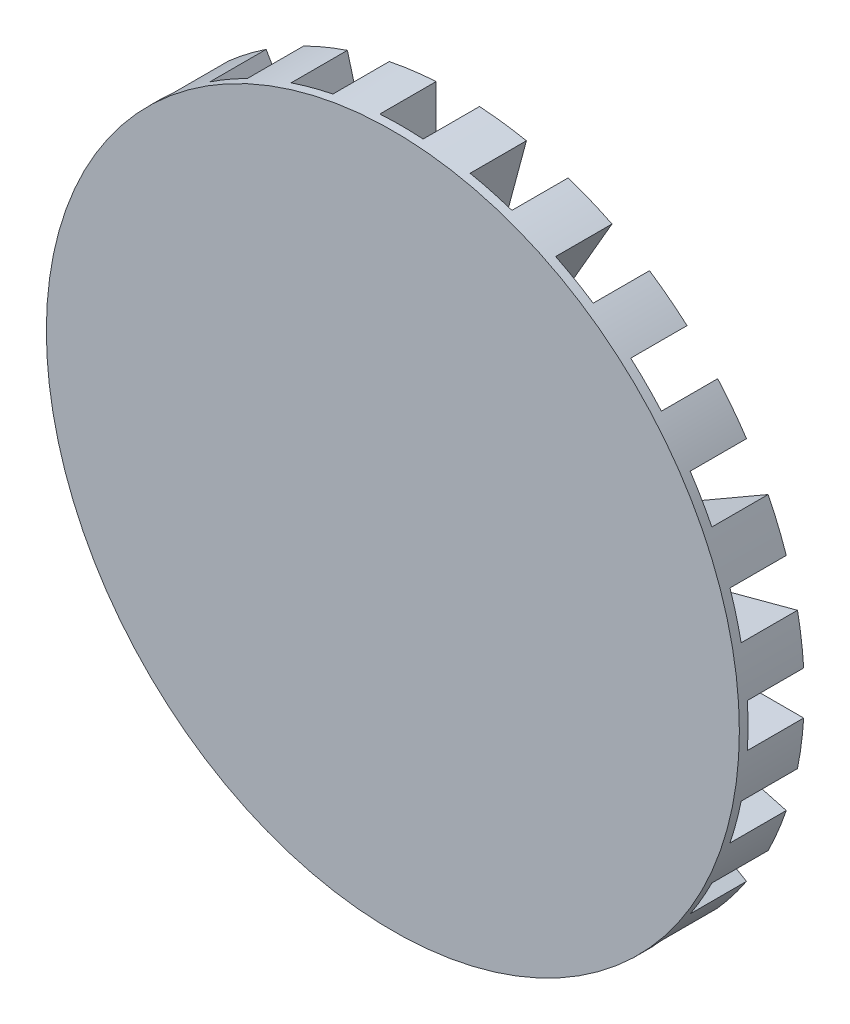
SolidWorks part; units mm, degrees
material "PUR"
ref_plane "Front Plane" through (0, 0, 0) normal (0, 0, 1) x (1, 0, 0)
ref_plane "Top Plane" through (0, 0, 0) normal (0, 1, 0) x (1, 0, 0)
ref_plane "Right Plane" through (0, 0, 0) normal (1, 0, 0) x (0, 0, -1)
sketch "Sketch1" plane through (0, 0, 0) normal (0, 0, 1) x (1, 0, 0)
  circle A0 centre (0, 0) radius 80
  circle A1 centre (0, 0) radius 100 construction
  circle A4 centre (0, 0) radius 100 construction
  dimension "D1" = 20
extrude "Boss-Extrude1" add sketch "Sketch1" along normal blind 2 from offset 13
sketch "Sketch3" plane through (0, 0, 15) normal (0, 0, 1) x (1, 0, 0)
  line L0 (0, 0) -> (0, -80) construction
  line L1 (0, 0) -> (-20.7055, -77.2741) construction
  line L2 (-5, -79.8436) -> (-5, -37.9788)
  line L3 (-5, -37.9788) -> (-15.8354, -78.4171)
  line L4 (-5, -58.9112) -> (0, -58.9112) construction
  line L5 (-10.4177, -58.1979) -> (-15.2473, -56.9038) construction
  circle A0 centre (0, 0) radius 80 construction
  arc A1 (-5, -79.8436) -> (-15.8354, -78.4171) centre (0, 0) cw
  dimension "D1" = 10
  dimension "D2" = 15
extrude "Boss-Extrude2" add sketch "Sketch3" against normal up to surface (15 mm away)
pattern_circular "CirPattern1" count 24 over 360 about axis through (0, 0, 0) along (0, 0, 1) of "Boss-Extrude2"
